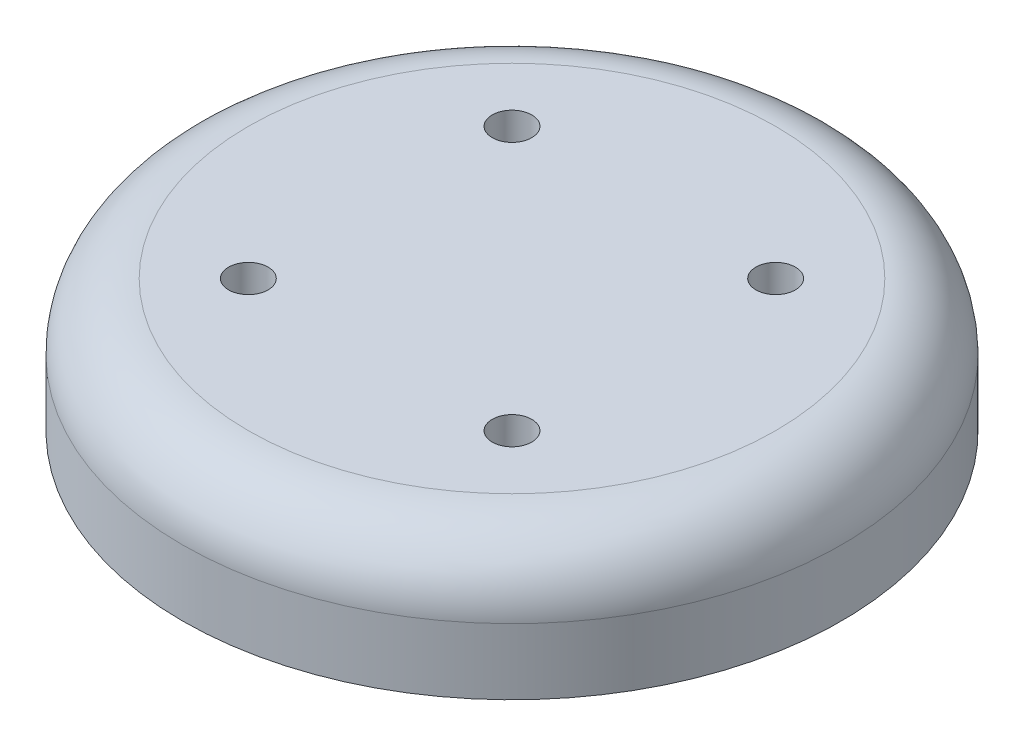
SolidWorks part; units mm, degrees
ref_plane "Front Plane" through (0, 0, 0) normal (0, 0, 1) x (1, 0, 0)
ref_plane "Top Plane" through (0, 0, 0) normal (0, 1, 0) x (1, 0, 0)
ref_plane "Right Plane" through (0, 0, 0) normal (1, 0, 0) x (0, 0, -1)
sketch "Sketch1" plane through (0, 0, 0) normal (0, 1, 0) x (1, 0, 0)
  circle A0 centre (0, 0) radius 25
extrude "Boss-Extrude1" add sketch "Sketch1" along normal blind 10
fillet "Fillet1" radius 5 1 edges at (0, 10, 25)
sketch "Sketch2" plane through (0, 10, 0) normal (0, 1, 0) x (1, 0, 0)
  line L5 (-10, 10) -> (10, -10) construction
  line L6 (-10, -10) -> (10, 10) construction
  circle A0 centre (-10, 10) radius 1.5
  circle A1 centre (10, 10) radius 1.5
  circle A2 centre (-10, -10) radius 1.5
  circle A3 centre (10, -10) radius 1.5
  point P0 (0, 0)
  point P20 (0, 0)
extrude "Cut-Extrude1" cut sketch "Sketch2" against normal through all
sketch "Sketch3" plane through (0, 0, 0) normal (0, -1, 0) x (1, 0, 0)
  circle A0 centre (0, 0) radius 20
extrude "Cut-Extrude2" cut sketch "Sketch3" against normal blind 5
